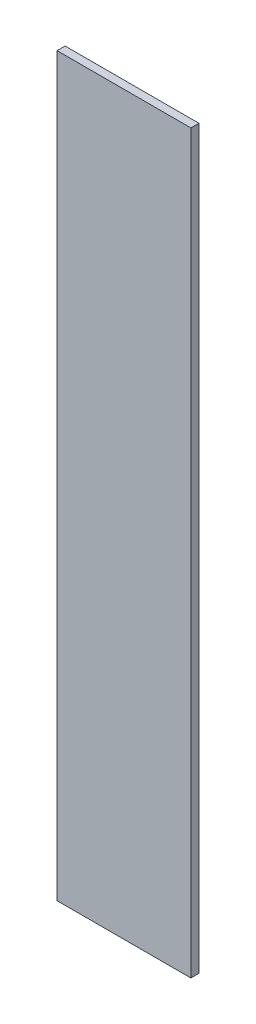
SolidWorks part; units mm, degrees
ref_plane "Plan de face" through (0, 0, 0) normal (0, 0, 1) x (1, 0, 0)
ref_plane "Plan de dessus" through (0, 0, 0) normal (0, 1, 0) x (1, 0, 0)
ref_plane "Plan de droite" through (0, 0, 0) normal (1, 0, 0) x (0, 0, -1)
sketch "Esquisse1" plane through (0, 0, 0) normal (0, 0, 1) x (1, 0, 0)
  line L1 (-22.8054, 65.6792) -> (27.1946, 65.6792)
  line L2 (-22.8054, 65.6792) -> (-22.8054, -209.3208)
  line L3 (-22.8054, -209.3208) -> (27.1946, -209.3208)
  line L4 (27.1946, 65.6792) -> (27.1946, -209.3208)
  dimension "D1" = 275
  dimension "D2" = 50
extrude "Boss.-Extru.1" add sketch "Esquisse1" along normal blind 3
